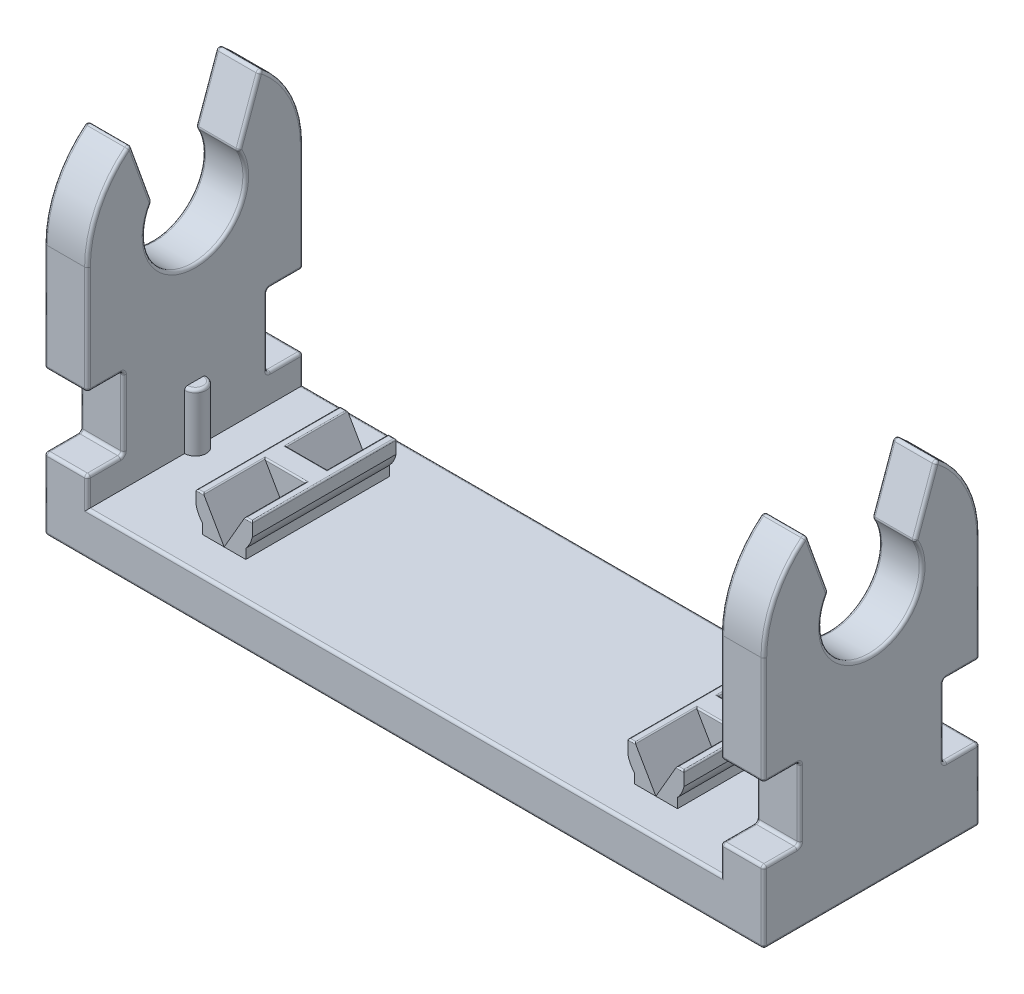
SolidWorks part; units mm, degrees
ref_plane "前视基准面" through (0, 0, 0) normal (0, 0, 1) x (1, 0, 0)
ref_plane "上视基准面" through (0, 0, 0) normal (0, 1, 0) x (1, 0, 0)
ref_plane "右视基准面" through (0, 0, 0) normal (1, 0, 0) x (0, 0, -1)
sketch "草图1" plane through (0, 0, 0) normal (1, 0, 0) x (0, 0, -1)
  line L0 (0, 0) -> (0, 17.5) construction
  line L1 (7.5, 0) -> (-7.5, 0)
  line L2 (-7.5, 0) -> (-7.5, 5)
  line L3 (-7.5, 5) -> (-5, 5)
  line L4 (-5, 5) -> (-5, 10)
  line L5 (-5, 10) -> (-7.5, 10)
  line L6 (-7.5, 10) -> (-7.5, 17.5)
  line L7 (0, 17.5) -> (-3, 17.5) construction
  line L8 (-3, 17.5) -> (-3, 19.3028) construction
  line L9 (0, 17.5) -> (-4.5, 17.5) construction
  line L10 (-4.5, 17.5) -> (-4.5, 23.5) construction
  line L11 (-4.5, 23.5) -> (-3, 19.3028)
  line L12 (7.5, 0) -> (7.5, 5)
  line L13 (7.5, 5) -> (5, 5)
  line L14 (5, 5) -> (5, 10)
  line L15 (5, 10) -> (7.5, 10)
  line L16 (7.5, 10) -> (7.5, 17.5)
  line L17 (4.5, 23.5) -> (3, 19.3028)
  arc A0 (-3, 19.3028) -> (3, 19.3028) centre (0, 17.5) ccw
  arc A1 (-4.5, 23.5) -> (-7.5, 17.5) centre (0, 17.5) ccw
  arc A2 (4.5, 23.5) -> (7.5, 17.5) centre (0, 17.5) cw
  dimension "D2" = 7
  dimension "D8" = 15
  dimension "D1" = 17.5
  dimension "D3" = 7.5
  dimension "D4" = 5
  dimension "D5" = 5
  dimension "D6" = 5
  dimension "D7" = 7.5
  dimension "D9" = 3
  dimension "D10" = 4.5
  dimension "D11" = 90
extrude "凸台-拉伸1" add sketch "草图1" along normal blind 50
sketch "草图2" plane through (0, 0, 0) normal (0, 0, 1) x (1, 0, 0)
  line L0 (50, 0) -> (0, 0) construction
  line L1 (3, 3) -> (47, 3)
  line L2 (3, 3) -> (3, 25)
  line L3 (3, 25) -> (47, 25)
  line L4 (47, 3) -> (47, 25)
  line L5 (0, 10) -> (0, 5) construction
  line L6 (50, 10) -> (50, 5) construction
  dimension "D1" = 3
  dimension "D2" = 3
  dimension "D3" = 3
  dimension "D4" = 22
extrude "切除-拉伸1" cut sketch "草图2" against normal up to next and the other way up to next
sketch "草图3" plane through (0, 0, 0) normal (0, 0, 1) x (1, 0, 0)
  line L0 (25, 0) -> (25, -2) construction
  line L1 (50, 0) -> (0, 0) construction
  line L2 (25, -2) -> (25, -2.5) construction
  line L3 (26.5, 0) -> (23.5, 0)
  line L4 (23.5, 0) -> (23.5, -0.6771)
  line L5 (26.95, -2.5) -> (23.05, -2.5)
  line L6 (23.05, -2.5) -> (23.05, -1.5556)
  line L7 (26.95, -2.5) -> (26.95, -1.5556)
  line L8 (26.5, 0) -> (26.5, -0.6771)
  arc A0 (23.5, -0.6771) -> (23.05, -1.5556) centre (25, -2) ccw
  arc A1 (26.5, -0.6771) -> (26.95, -1.5556) centre (25, -2) cw
  dimension "D5" = 2
  dimension "D1" = 2
  dimension "D2" = 0.5
  dimension "D3" = 1.5
  dimension "D4" = 1.95
extrude "凸台-拉伸2" add sketch "草图3" along normal blind 2 and the other way blind 2
pattern_linear "阵列(线性)1" count 2 spacing 15 along (-1, 0, 0) count 2 spacing 15 along (1, 0, 0) of "凸台-拉伸2"
sketch "草图4" plane through (0, 0, 0) normal (-1, 0, 0) x (0, 0, 1)
  line L0 (0, 0) -> (0, -2) construction
  line L1 (0, -2) -> (0, -2.5) construction
  line L2 (-2, -2.5) -> (2, -2.5) construction
  line L3 (0, 0) -> (1.5, 0) construction
  line L4 (-2, 0) -> (2, 0) construction
  line L5 (1.5, 0) -> (1.5, -0.6771)
  line L6 (0, -2.5) -> (1.95, -2.5) construction
  line L7 (1.95, -2.5) -> (1.95, -1.5556)
  line L8 (1.5, 0) -> (2, 0)
  line L9 (2, 0) -> (2, -2.5)
  line L10 (2, -2.5) -> (1.95, -2.5)
  line L11 (-2, -2.5) -> (-1.95, -2.5)
  line L12 (-2, 0) -> (-2, -2.5)
  line L13 (-1.5, 0) -> (-2, 0)
  line L14 (-1.95, -2.5) -> (-1.95, -1.5556)
  line L15 (-1.5, 0) -> (-1.5, -0.6771)
  arc A0 (1.95, -1.5556) -> (1.5, -0.6771) centre (0, -2) ccw
  arc A1 (-1.95, -1.5556) -> (-1.5, -0.6771) centre (0, -2) cw
  dimension "D1" = 2
  dimension "D2" = 1.5
  dimension "D3" = 1.95
extrude "切除-拉伸2" cut sketch "草图4" against normal blind 50
sketch "草图5" plane through (0, 0, 0) normal (0, 0, 1) x (1, 0, 0)
  line L0 (10, 3) -> (10, 5) construction
  line L1 (47, 3) -> (3, 3) construction
  line L2 (10, 5) -> (10, 5.5) construction
  line L3 (10, 3) -> (8.5, 3)
  line L4 (8.5, 3) -> (8.5, 3.6771)
  line L5 (8.5566, 5.5) -> (8.05, 5.5)
  line L6 (8.05, 5.5) -> (8.05, 4.5556)
  line L7 (10, 3) -> (8.5566, 5.5)
  arc A0 (8.05, 4.5556) -> (8.5, 3.6771) centre (10, 5) ccw
  dimension "D6" = 2
  dimension "D1" = 10
  dimension "D2" = 2
  dimension "D3" = 0.5
  dimension "D4" = 1.5
  dimension "D5" = 1.95
  dimension "D7" = 30
extrude "凸台-拉伸3" add sketch "草图5" along normal blind 5 and the other way blind 5
ref_plane "基准面1" through (10, 0, 0) normal (1, 0, 0) x (0, 0, -1)
mirror "镜向1" about plane through (10, 0, 0) normal (1, 0, 0) of "凸台-拉伸3"
sketch "草图6" plane through (0, 5.5, 0) normal (0, 1, 0) x (1, 0, 0)
  line L0 (8.5566, 0) -> (11.4434, 0) construction
  line L1 (8.5566, 5) -> (8.5566, -5) construction
  line L2 (11.4434, 5) -> (11.4434, -5) construction
  line L3 (8.5566, -0.75) -> (11.4434, -0.75)
  line L4 (8.5566, 0.75) -> (11.4434, 0.75)
  line L5 (8.5566, 0.75) -> (8.5566, -0.75)
  line L6 (11.4434, 0.75) -> (11.4434, -0.75)
  dimension "D1" = 0.75
  dimension "D2" = 0.75
extrude "凸台-拉伸4" add sketch "草图6" against normal blind 2.5
sketch "草图7" plane through (0, 3, 0) normal (0, 1, 0) x (1, 0, 0)
  line L0 (3, -3.5) -> (3, 3.5) construction
  circle A0 centre (3, 0) radius 0.75
  dimension "D1" = 1.5
extrude "凸台-拉伸5" add sketch "草图7" along normal blind 4
pattern_linear "阵列(线性)2" count 2 spacing 30 along (1, 0, 0) of "凸台-拉伸4", "镜向1", "凸台-拉伸3"
ref_plane "基准面2" through (25, 0, 0) normal (-1, 0, 0) x (0, 0, 1)
mirror "镜向2" about plane through (25, 0, 0) normal (-1, 0, 0) of "凸台-拉伸5"
fillet "圆角1" radius 0.1 12 edges at (11.95, -2.5, 0) (10, -2.5, -1.95) (8.05, -2.5, 0) (10, -2.5, 1.95) (26.95, -2.5, 0) (25, -2.5, -1.95) (23.05, -2.5, 0) (25, -2.5, 1.95) (41.95, -2.5, 0) (40, -2.5, -1.95) (38.05, -2.5, 0) (40, -2.5, 1.95)
fillet "圆角2" radius 0.2 90 edges at (3, 5, -6.25) (1.5, 5, -5) (3, 7.5, -5) (1.5, 10, -5) (3, 10, -6.25) (1.5, 10, -7.5) (3, 13.75, -7.5) (3, 20.8541, -6.7082) (1.5, 23.5, -4.5) (3, 21.4014, -3.75) (1.5, 19.3028, -3) (3, 14, 0) (1.5, 19.3028, 3) (3, 21.4014, 3.75) (1.5, 23.5, 4.5) (3, 20.8541, 6.7082) (3, 13.75, 7.5) (1.5, 10, 7.5) (3, 10, 6.25) (1.5, 10, 5) (3, 7.5, 5) (1.5, 5, 5) (3, 5, 6.25) (25, 3, 7.5) (47, 4, 7.5) (25, 0, 7.5) (1.5, 5, 7.5) (3, 4, 7.5) (48.5, 5, 7.5) (47, 5, 6.25) (48.5, 5, 5) (47, 7.5, 5) (48.5, 10, 5) (47, 10, 6.25) (47, 21.4014, -3.75) (48.5, 10, 7.5) (47, 13.75, 7.5) (47, 20.8541, 6.7082) (48.5, 23.5, 4.5) (47, 21.4014, 3.75) (48.5, 19.3028, -3) (48.5, 19.3028, 3) (47, 14, 0) (48.5, 23.5, -4.5) (47, 20.8541, -6.7082) (47, 13.75, -7.5) (48.5, 10, -7.5) (47, 10, -6.25) (47, 5, -6.25) (48.5, 5, -5) (48.5, 10, -5) (47, 7.5, -5) (1.5, 5, -7.5) (25, 0, -7.5) (48.5, 5, -7.5) (47, 4, -7.5) (25, 3, -7.5) (3, 4, -7.5) (0, 5, -6.25) (0, 7.5, -5) (0, 10, -6.25) (0, 13.75, -7.5) (0, 20.8541, -6.7082) (0, 21.4014, -3.75) (0, 14, 0) (0, 21.4014, 3.75) (0, 20.8541, 6.7082) (0, 13.75, 7.5) (0, 10, 6.25) (0, 7.5, 5) (0, 5, 6.25) (0, 2.5, 7.5) (0, 0, 0) (0, 2.5, -7.5) (50, 0, 0) (50, 2.5, 7.5) (50, 5, 6.25) (50, 7.5, 5) (50, 10, 6.25) (50, 13.75, 7.5) (50, 20.8541, 6.7082) (50, 21.4014, 3.75) (50, 14, 0) (50, 21.4014, -3.75) (50, 20.8541, -6.7082) (50, 13.75, -7.5) (50, 10, -6.25) (50, 7.5, -5) (50, 5, -6.25) (50, 2.5, -7.5)
fillet "圆角3" radius 0.2 2 edges at (3.75, 7, 0) (46.25, 7, 0)
fillet "圆角4" radius 0.1 24 edges at (38.3033, 5.5, -5) (38.5566, 5.5, -2.875) (40, 5.5, -0.75) (41.4434, 5.5, -2.875) (41.6967, 5.5, -5) (41.95, 5.5, 0) (41.6967, 5.5, 5) (41.4434, 5.5, 2.875) (40, 5.5, 0.75) (38.5566, 5.5, 2.875) (38.3033, 5.5, 5) (38.05, 5.5, 0) (8.3033, 5.5, -5) (8.5566, 5.5, -2.875) (10, 5.5, -0.75) (11.4434, 5.5, -2.875) (11.6967, 5.5, -5) (11.95, 5.5, 0) (11.6967, 5.5, 5) (11.4434, 5.5, 2.875) (10, 5.5, 0.75) (8.5566, 5.5, 2.875) (8.3033, 5.5, 5) (8.05, 5.5, 0)
